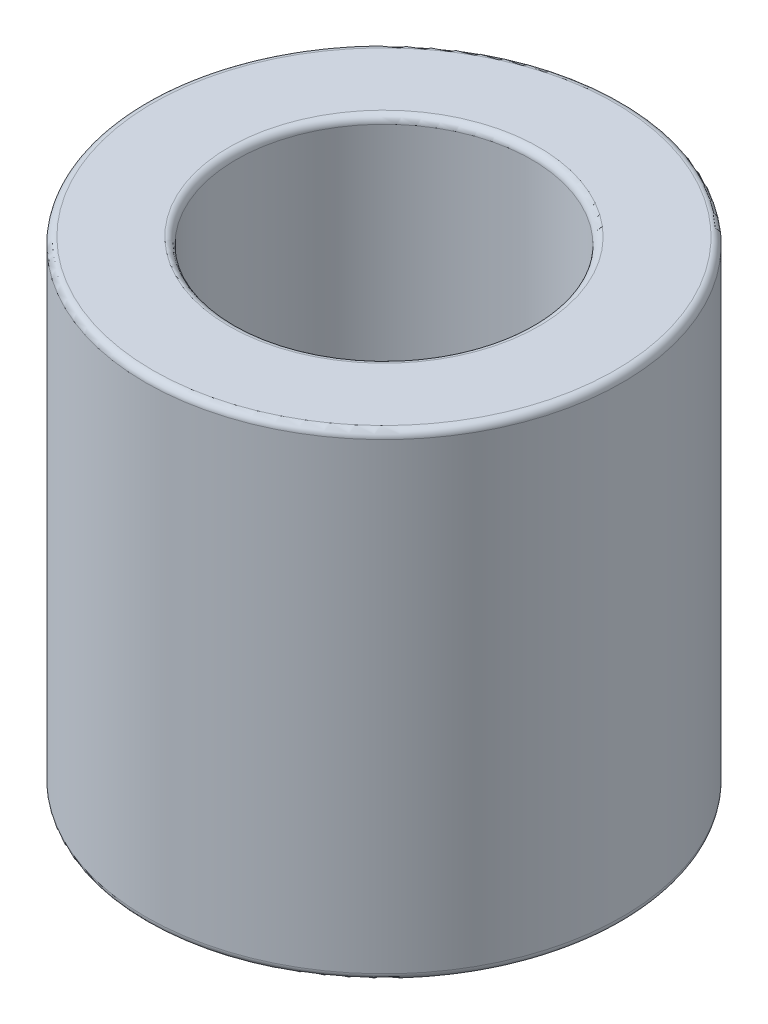
SolidWorks part; units mm, degrees
material "6061 Alloy"
ref_plane "Front Plane" through (0, 0, 0) normal (0, 0, 1) x (1, 0, 0)
ref_plane "Top Plane" through (0, 0, 0) normal (0, 1, 0) x (1, 0, 0)
ref_plane "Right Plane" through (0, 0, 0) normal (1, 0, 0) x (0, 0, -1)
sketch "Sketch1" plane through (0, 0, 0) normal (0, 1, 0) x (1, 0, 0)
  circle A0 centre (0, 0) radius 5
  circle A1 centre (0, 0) radius 3.1
  dimension "D1" = 10
  dimension "D2" = 6.2
extrude "Boss-Extrude1" add sketch "Sketch1" along normal blind 10
fillet "Fillet1" radius 0.15 4 edges at (0, 0, 3.1) (0, 0, 5) (0, 10, 3.1) (0, 10, 5)
